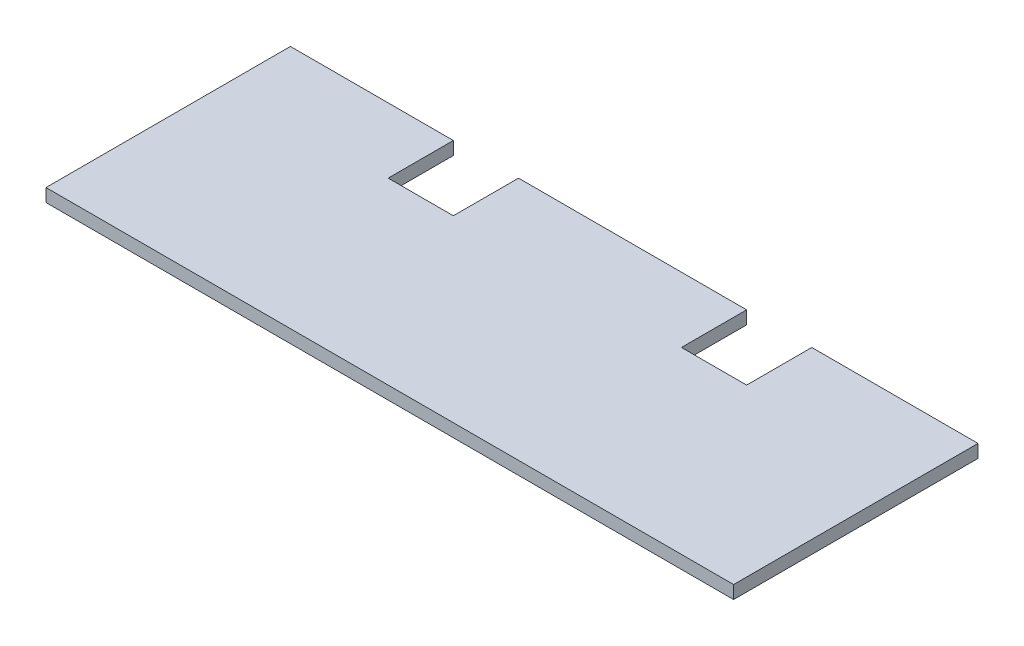
SolidWorks part; units mm, degrees
ref_plane "Front Plane" through (0, 0, 0) normal (0, 0, 1) x (1, 0, 0)
ref_plane "Top Plane" through (0, 0, 0) normal (0, 1, 0) x (1, 0, 0)
ref_plane "Right Plane" through (0, 0, 0) normal (1, 0, 0) x (0, 0, -1)
sketch "Sketch1" plane through (0, 0, 0) normal (0, 1, 0) x (1, 0, 0)
  line L1 (-105.5, -37.5) -> (105.5, -37.5)
  line L2 (-105.5, -37.5) -> (-105.5, 37.5)
  line L3 (-105.5, 37.5) -> (105.5, 37.5)
  line L4 (105.5, -37.5) -> (105.5, 37.5)
  line L5 (-105.5, -37.5) -> (105.5, 37.5) construction
  line L6 (-105.5, 37.5) -> (105.5, -37.5) construction
  point P0 (0, 0)
  dimension "D1" = 75
  dimension "D2" = 211
extrude "Boss-Extrude1" add sketch "Sketch1" along normal blind 4
sketch "Sketch3" plane through (0, 4, 0) normal (0, 1, 0) x (1, 0, 0)
  line L0 (-105.5, 37.5) -> (-105.5, -37.5) construction
  line L1 (-55.5, 37.5) -> (-55.5, 17.5)
  line L2 (-55.5, 17.5) -> (-35.5, 17.5)
  line L3 (-35.5, 21.1733) -> (-35.5, 37.5)
  line L4 (105.5, 37.5) -> (-105.5, 37.5) construction
  line L5 (-35.5, 17.5) -> (-35.5, 21.1733)
  line L6 (-35.5, 37.5) -> (-55.5, 37.5)
  dimension "D1" = 20
  dimension "D2" = 0
  dimension "D3" = 50
  dimension "D4" = 20
extrude "Cut-Extrude2" cut sketch "Sketch3" against normal up to next
sketch "Sketch5" plane through (0, 4, 0) normal (0, 1, 0) x (1, 0, 0)
  line L0 (-45.5, 17.5) -> (44.5, 17.5) construction
  line L1 (-55.5, 17.5) -> (-35.5, 17.5) construction
  line L2 (44.5, 17.5) -> (54.5, 17.5)
  line L3 (54.5, 17.5) -> (54.5, 37.5)
  line L4 (105.5, 37.5) -> (-35.5, 37.5) construction
  line L5 (54.5, 37.5) -> (34.5, 37.5)
  line L6 (34.5, 37.5) -> (34.5, 17.5)
  line L7 (34.5, 17.5) -> (44.5, 17.5)
  dimension "D1" = 20
  dimension "D2" = 10
  dimension "D3" = 90
extrude "Cut-Extrude3" cut sketch "Sketch5" against normal up to next
